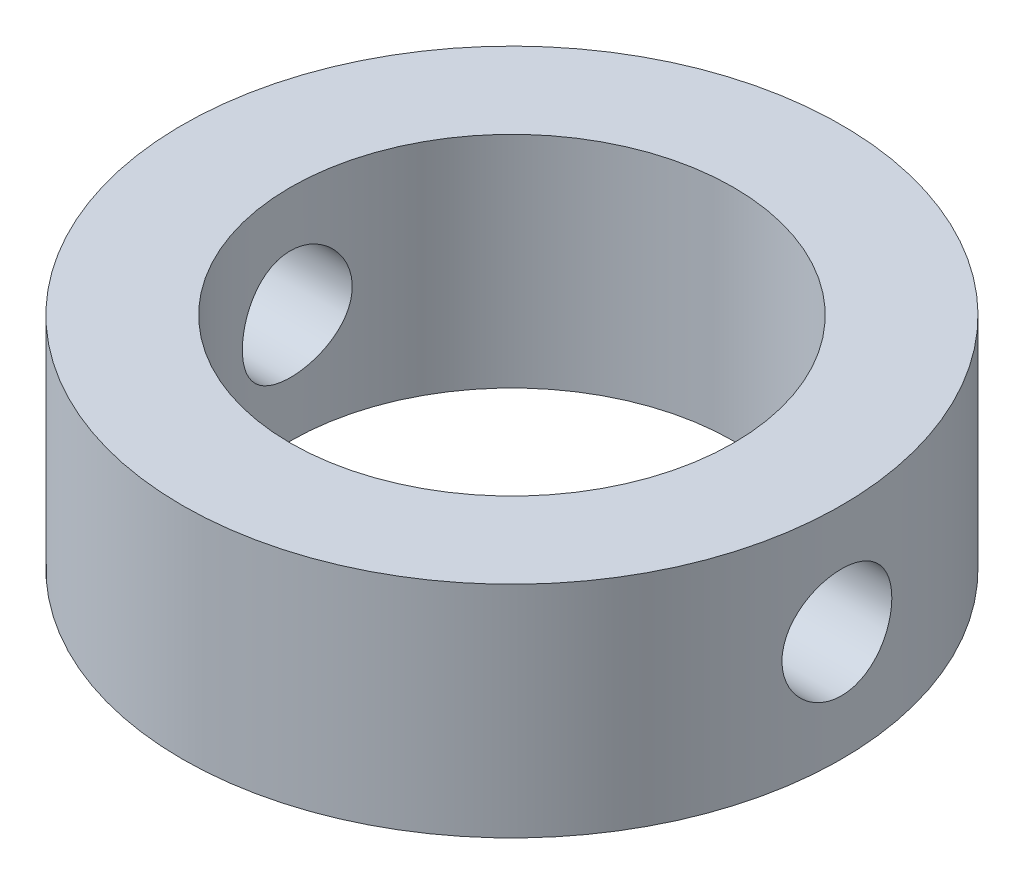
SolidWorks part; units mm, degrees
other "Rear Axle Collar"
ref_plane "Front Plane" through (0, 0, 0) normal (0, 0, 1) x (1, 0, 0)
ref_plane "Top Plane" through (0, 0, 0) normal (0, 1, 0) x (1, 0, 0)
ref_plane "Right Plane" through (0, 0, 0) normal (1, 0, 0) x (0, 0, -1)
sketch3d "Collar stock sketch datum points"
  point P0 (-19.0092, -246.5, -53.2449)
  point P1 (-9.0092, -246.5, -53.2449)
  point P2 (-19.0092, -246.5, -63.2449)
ref_plane "Collar stock sketch plane" through (0, -246.5, 0) normal (0, 1, 0) x (1, 0, 0)
sketch "Collar stock sketch" plane through (0, -246.5, 0) normal (0, 1, 0) x (1, 0, 0)
  circle A0 centre (-19.0092, 53.2449) radius 9
extrude "Collar stock" add sketch "Collar stock sketch" along normal blind 6 separate body
sketch3d "Axle collar bore sketch datum points"
  point P0 (-19.0092, -246.6, -53.2449)
  point P1 (-9.0092, -246.6, -53.2449)
  point P2 (-19.0092, -246.6, -63.2449)
ref_plane "Axle collar bore sketch plane" through (0, -246.6, 0) normal (0, 1, 0) x (1, 0, 0)
sketch "Axle collar bore sketch" plane through (0, -246.6, 0) normal (0, 1, 0) x (1, 0, 0)
  circle A0 centre (-19.0092, 53.2449) radius 6.05
extrude "Axle collar bore" cut sketch "Axle collar bore sketch" along normal blind 6.2
sketch3d "Positive spring pin bore sketch datum points"
  point P0 (-29.0092, -243.5, -53.2449)
  point P1 (-29.0092, -233.5, -53.2449)
  point P2 (-29.0092, -243.5, -43.2449)
ref_plane "Positive spring pin bore sketch plane" through (-29.0092, 0, 0) normal (1, 0, 0) x (0, 0, -1)
sketch "Positive spring pin bore sketch" plane through (-29.0092, 0, 0) normal (1, 0, 0) x (0, 0, -1)
  circle A0 centre (53.2449, -243.5) radius 1.5
extrude "Positive spring pin bore" cut sketch "Positive spring pin bore sketch" along normal blind 20
